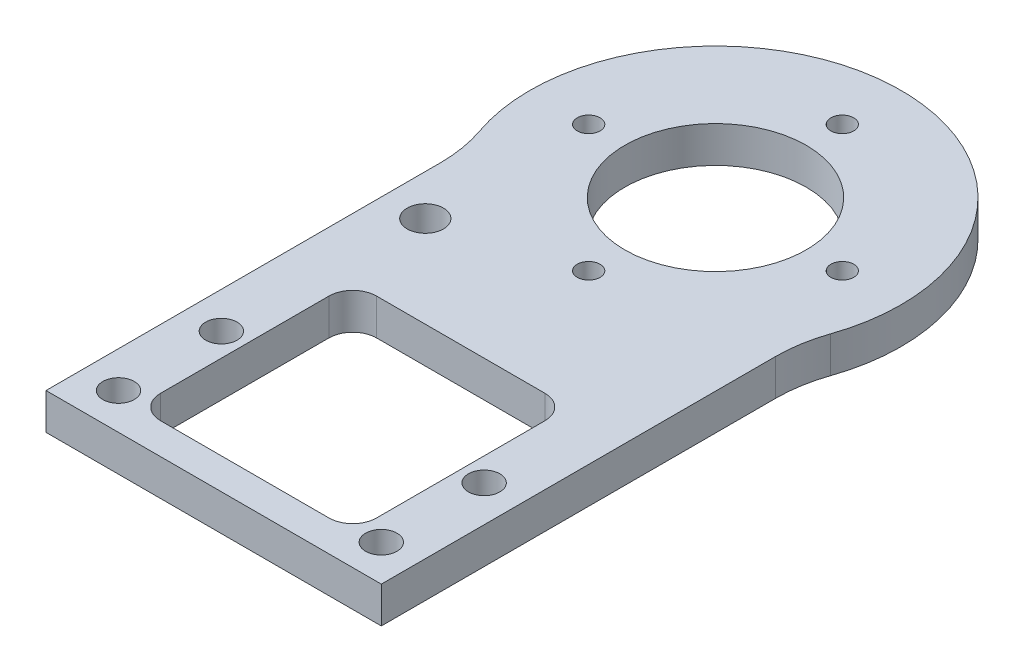
SolidWorks part; units mm, degrees
ref_plane "Front Plane" through (0, 0, 0) normal (0, 0, 1) x (1, 0, 0)
ref_plane "Top Plane" through (0, 0, 0) normal (0, 1, 0) x (1, 0, 0)
ref_plane "Right Plane" through (0, 0, 0) normal (1, 0, 0) x (0, 0, -1)
sketch "Sketch1" plane through (0, 199.6315, 0) normal (0, -1, 0) x (1, 0, 0)
  line L0 (-14.7394, -54.7041) -> (14.7394, -54.7041) construction
  line L1 (-17, -86.4435) -> (-17, -56.9647) construction
  line L2 (17, -56.9647) -> (17, -86.4435) construction
  line L3 (-14.7394, -54.7041) -> (14.7394, -54.7041) construction
  line L4 (-17, -86.4435) -> (-17, -56.9647) construction
  line L5 (17, -56.9647) -> (17, -86.4435) construction
  line L6 (14.7394, -88.7041) -> (-14.7394, -88.7041) construction
  line L7 (14.7394, -88.7041) -> (-14.7394, -88.7041) construction
  line L8 (17, -71.7041) -> (-17, -71.7041) construction
  line L9 (0, -71.7041) -> (0, -135.2041) construction
  line L11 (-14.7394, -52.7991) -> (14.7394, -52.7991)
  line L13 (14.7394, -90.6091) -> (-14.7394, -90.6091)
  line L18 (0, -71.7041) -> (0, -47.3541) construction
  line L19 (-29.35, -47.3541) -> (29.35, -47.3541)
  line L20 (29.35, -47.3541) -> (29.35, -116.3667)
  line L21 (-29.35, -47.3541) -> (-29.35, -116.3667)
  line L22 (0, -135.2041) -> (-22.2, -135.2041) construction
  line L23 (18.905, -56.9647) -> (18.905, -86.4435)
  line L24 (18.905, -56.9647) -> (17, -56.9647) construction
  line L25 (17, -86.4435) -> (18.905, -86.4435) construction
  line L27 (-18.905, -56.9647) -> (-18.905, -86.4435)
  circle A0 centre (-23, -71.7041) radius 2.75 construction
  circle A1 centre (-23, -53.7041) radius 2.75 construction
  circle A2 centre (23, -53.7041) radius 2.75 construction
  circle A3 centre (23, -71.7041) radius 2.75 construction
  circle A4 centre (-23, -71.7041) radius 2.75
  circle A5 centre (-23, -53.7041) radius 2.75
  circle A6 centre (23, -53.7041) radius 2.75
  circle A7 centre (23, -71.7041) radius 2.75
  circle A8 centre (0, -135.2041) radius 15.875
  circle A9 centre (-22.2, -135.2041) radius 2
  circle A10 centre (0, -113.0041) radius 2
  circle A11 centre (22.2, -135.2041) radius 2
  circle A12 centre (0, -157.4041) radius 2
  arc A13 (30.7319, -124.6304) -> (-30.7319, -124.6304) centre (0, -135.2041) cw
  arc A14 (30.7319, -124.6304) -> (29.35, -116.3667) centre (54.75, -116.3667) cw
  arc A15 (-30.7319, -124.6304) -> (-29.35, -116.3667) centre (-54.75, -116.3667) ccw
  arc A16 (-18.905, -56.9647) -> (-14.7394, -52.7991) centre (-14.7394, -56.9647) cw
  arc A17 (-18.905, -86.4435) -> (-14.7394, -90.6091) centre (-14.7394, -86.4435) ccw
  arc A18 (18.905, -56.9647) -> (14.7394, -52.7991) centre (14.7394, -56.9647) ccw
  arc A19 (18.905, -86.4435) -> (14.7394, -90.6091) centre (14.7394, -86.4435) cw
  point P50 (0, -135.2041)
  point P52 (29.35, -121.246)
  point P55 (-29.35, -121.246)
  dimension "D5" = 31.75
  dimension "D8" = 4
  dimension "D11" = 32.5
  dimension "D12" = 25.4
  dimension "D1" = 63.5
  dimension "D3" = 6.35
  dimension "D4" = 6.35
  dimension "D7" = 22.2
  dimension "D10" = 1.905
  dimension "D2" = 1.905
  dimension "D9" = 4
extrude "Boss-Extrude1" add sketch "Sketch1" along normal blind 6.35
sketch "Sketch2" plane through (0, 193.2815, 0) normal (0, -1, 0) x (1, 0, 0)
  line L0 (12.5783, -137.6114) -> (24.3021, -76.3553) construction
  line L2 (-12.783, -134.4264) -> (-11.133, -107.3038) construction
  line L3 (-21.939, -83.1455) -> (-12.3719, -101.4906) construction
  circle A0 centre (0, -135.2041) radius 12.8066 construction
  arc A1 (-12.783, -134.4264) -> (12.5783, -137.6114) centre (0, -135.2041) ccw construction
  circle A2 centre (0, -71.7041) radius 24.7432 construction
  arc A3 (24.3021, -76.3553) -> (-21.939, -83.1455) centre (0, -71.7041) ccw construction
  arc A4 (24.3021, -76.3553) -> (-21.939, -83.1455) centre (0, -71.7041) ccw construction
  circle A5 centre (-22.225, -106.6291) radius 3.175
  arc A6 (17.8156, -115.5863) -> (-17.8156, -115.5863) centre (0, -135.2041) ccw construction
  arc A7 (17.8156, -115.5863) -> (-17.8156, -115.5863) centre (0, -135.2041) ccw construction
  arc A8 (-11.133, -107.3038) -> (-12.3719, -101.4906) centre (-22.225, -106.6291) ccw construction
  circle A11 centre (-22.225, -106.6291) radius 11.1125 construction
  circle A12 centre (-22.225, -106.6291) radius 11.1125 construction
  dimension "D1" = 6.35
  dimension "D2" = 28.575
  dimension "D3" = 22.225
extrude "Cut-Extrude1" cut sketch "Sketch2" against normal through all
